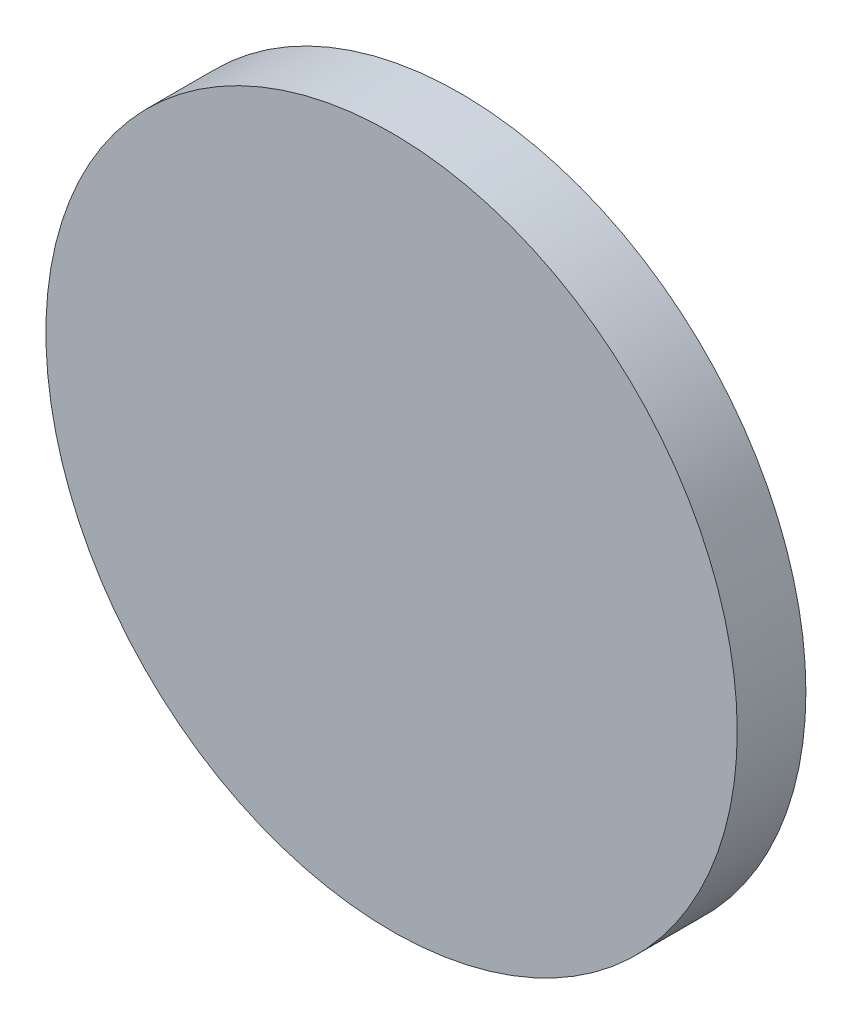
SolidWorks part; units mm, degrees
ref_plane "前视基准面" through (0, 0, 0) normal (0, 0, 1) x (1, 0, 0)
ref_plane "上视基准面" through (0, 0, 0) normal (0, 1, 0) x (1, 0, 0)
ref_plane "右视基准面" through (0, 0, 0) normal (1, 0, 0) x (0, 0, -1)
other "Configuration Table"
sketch "草图1" plane through (0, 0, 0) normal (0, 1, 0) x (1, 0, 0)
  line L0 (0, 0) -> (10, 0)
  line L1 (10, 0) -> (10, 1.9866)
  line L2 (10, 1.9866) -> (0, 1.9866) construction
  line L3 (0, 1.9866) -> (0, 0)
  line L4 (0, 1.9866) -> (0, 4)
  arc A0 (10, 1.9866) -> (0, 4) centre (0, -21.84) ccw
  dimension "D3" = 25.84
  dimension "D1" = 10
  dimension "D2" = 4
  dimension "D4" = 1.9866
revolve "旋转1" add sketch "草图1" angle 360 about L4
